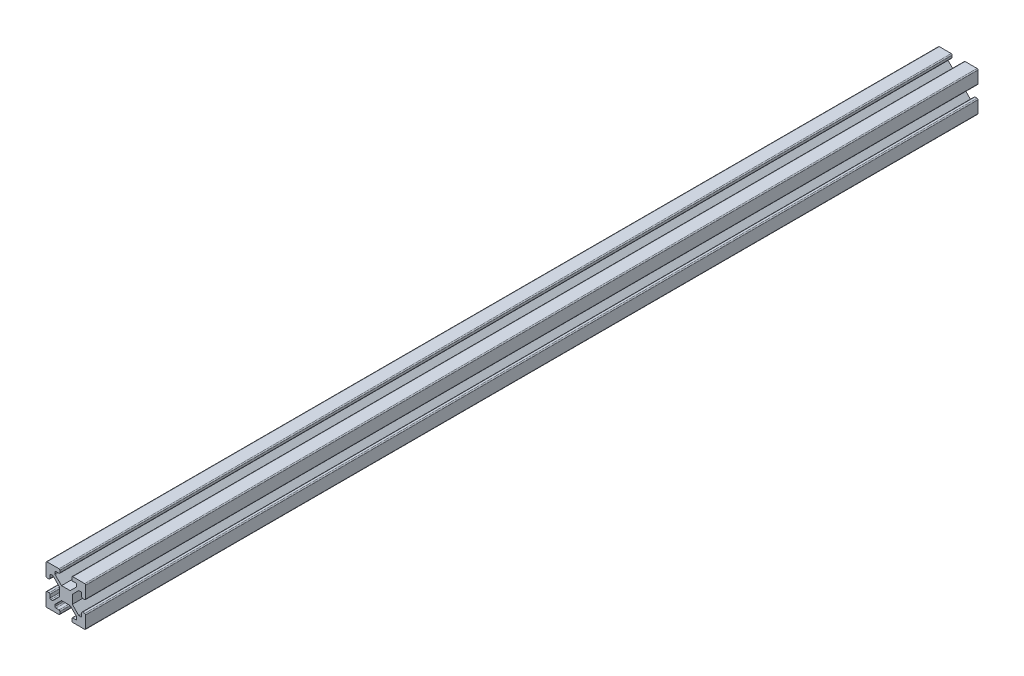
SolidWorks part; units mm, degrees
material "3.1645 (EN AW-2007)"
ref_plane "Front" through (0, 0, 0) normal (0, 0, 1) x (1, 0, 0)
ref_plane "Top" through (0, 0, 0) normal (0, 1, 0) x (1, 0, 0)
ref_plane "Right" through (0, 0, 0) normal (1, 0, 0) x (0, 0, -1)
sketch "草图1" plane through (0, 0, 0) normal (0, 0, 1) x (1, 0, 0)
  line L0 (6.5, 0) -> (0.5, 0)
  line L1 (20, -0.5) -> (20, -6.5)
  line L2 (19.5, -20) -> (13.5, -20)
  line L3 (20, -13.5) -> (20, -19.5)
  line L4 (13, -19.5) -> (13, -18.5)
  line L5 (13.5, -18) -> (15, -18)
  line L6 (15.5, -17.5) -> (15.5, -16.7791)
  line L7 (19.5, -7) -> (18.5, -7)
  line L8 (10, 0) -> (10, -26.2948) construction
  line L9 (18, -6.5) -> (18, -5)
  line L10 (17.5, -4.5) -> (16.7791, -4.5)
  line L11 (17.5, -15.5) -> (16.7791, -15.5)
  line L12 (18, -13.5) -> (18, -15)
  line L13 (19.5, -13) -> (18.5, -13)
  line L15 (0, -10) -> (20, -10) construction
  line L23 (4.5, -17.5) -> (4.5, -16.7791)
  line L24 (6.5, -18) -> (5, -18)
  line L25 (7, -19.5) -> (7, -18.5)
  line L27 (0.5, -20) -> (6.5, -20)
  line L29 (10, -20) -> (10, 6.2948) construction
  line L33 (0.5, -13) -> (1.5, -13)
  line L34 (2, -13.5) -> (2, -15)
  line L35 (2.5, -15.5) -> (3.2209, -15.5)
  line L36 (2.5, -4.5) -> (3.2209, -4.5)
  line L37 (2, -6.5) -> (2, -5)
  line L38 (0.5, -7) -> (1.5, -7)
  line L40 (7, -0.5) -> (7, -1.5)
  line L41 (6.5, -2) -> (5, -2)
  line L42 (4.5, -2.5) -> (4.5, -3.2209)
  line L43 (3.5745, -4.6464) -> (6.7416, -7.8136)
  line L44 (6.7416, -7.8136) -> (6.7416, -12.1864)
  line L45 (15.5, -2.5) -> (15.5, -3.2209)
  line L46 (13.5, -2) -> (15, -2)
  line L47 (13, -0.5) -> (13, -1.5)
  line L48 (19.5, 0) -> (13.5, 0)
  line L50 (10.3536, -10.3536) -> (20, -20) construction
  line L51 (4.6464, -3.5745) -> (7.8136, -6.7416)
  line L52 (7.8136, -6.7416) -> (12.1864, -6.7416)
  line L53 (0, -20) -> (9.6464, -10.3536) construction
  line L54 (15.3536, -3.5745) -> (12.1864, -6.7416)
  line L55 (13.2584, -7.8136) -> (13.2584, -12.1864)
  line L56 (16.4255, -4.6464) -> (13.2584, -7.8136)
  line L57 (10, 0) -> (10, -26.2948) construction
  line L58 (10, -20) -> (10, 6.2948) construction
  line L59 (16.4255, -15.3536) -> (13.2584, -12.1864)
  line L60 (15.3536, -16.4255) -> (12.3328, -13.4048)
  line L61 (8.0207, -13.2584) -> (11.9793, -13.2584)
  line L62 (4.6464, -16.4255) -> (7.6672, -13.4048)
  line L63 (3.5745, -15.3536) -> (6.7416, -12.1864)
  line L64 (0, -6.5) -> (0, -0.5)
  line L66 (0, -13.5) -> (0, -19.5)
  arc A0 (19.5, -7) -> (20, -6.5) centre (19.5, -6.5) ccw
  arc A1 (4.6464, -16.4255) -> (4.5, -16.7791) centre (5, -16.7791) ccw
  arc A2 (8.0207, -13.2584) -> (7.6672, -13.4048) centre (8.0207, -13.7584) ccw
  arc A3 (12.3328, -13.4048) -> (11.9793, -13.2584) centre (11.9793, -13.7584) ccw
  arc A4 (16.4255, -15.3536) -> (16.7791, -15.5) centre (16.7791, -15) ccw
  arc A5 (16.4255, -4.6464) -> (16.7791, -4.5) centre (16.7791, -5) cw
  arc A6 (15.3536, -16.4255) -> (15.5, -16.7791) centre (15, -16.7791) cw
  arc A7 (10.3536, -10.3536) -> (9.6464, -10.3536) centre (10, -10.7071) ccw construction
  arc A8 (15.3536, -3.5745) -> (15.5, -3.2209) centre (15, -3.2209) ccw
  arc A9 (3.5745, -15.3536) -> (3.2209, -15.5) centre (3.2209, -15) cw
  arc A10 (3.5745, -4.6464) -> (3.2209, -4.5) centre (3.2209, -5) ccw
  arc A11 (0.5, -7) -> (0, -6.5) centre (0.5, -6.5) cw
  arc A12 (2, -6.5) -> (1.5, -7) centre (1.5, -6.5) cw
  arc A13 (4.6464, -3.5745) -> (4.5, -3.2209) centre (5, -3.2209) cw
  arc A14 (2.5, -4.5) -> (2, -5) centre (2.5, -5) ccw
  arc A15 (2, -15) -> (2.5, -15.5) centre (2.5, -15) ccw
  arc A16 (1.5, -13) -> (2, -13.5) centre (1.5, -13.5) cw
  arc A17 (0.5, -13) -> (0, -13.5) centre (0.5, -13.5) ccw
  arc A18 (19.5, -13) -> (20, -13.5) centre (19.5, -13.5) cw
  arc A19 (13.5, 0) -> (13, -0.5) centre (13.5, -0.5) ccw
  arc A20 (13, -1.5) -> (13.5, -2) centre (13.5, -1.5) ccw
  arc A21 (15, -2) -> (15.5, -2.5) centre (15, -2.5) cw
  arc A22 (18, -13.5) -> (18.5, -13) centre (18.5, -13.5) cw
  arc A23 (4.5, -2.5) -> (5, -2) centre (5, -2.5) cw
  arc A24 (6.5, -2) -> (7, -1.5) centre (6.5, -1.5) ccw
  arc A25 (7, -0.5) -> (6.5, 0) centre (6.5, -0.5) ccw
  arc A26 (6.5, -18) -> (7, -18.5) centre (6.5, -18.5) cw
  arc A27 (4.5, -17.5) -> (5, -18) centre (5, -17.5) ccw
  arc A28 (17.5, -15.5) -> (18, -15) centre (17.5, -15) ccw
  arc A29 (15, -18) -> (15.5, -17.5) centre (15, -17.5) ccw
  arc A30 (13, -18.5) -> (13.5, -18) centre (13.5, -18.5) cw
  arc A31 (18, -5) -> (17.5, -4.5) centre (17.5, -5) ccw
  arc A32 (18.5, -7) -> (18, -6.5) centre (18.5, -6.5) cw
  arc A33 (19.5, 0) -> (20, -0.5) centre (19.5, -0.5) cw
  arc A34 (0.5, 0) -> (0, -0.5) centre (0.5, -0.5) ccw
  arc A35 (7, -19.5) -> (6.5, -20) centre (6.5, -19.5) cw
  arc A36 (13.5, -20) -> (13, -19.5) centre (13.5, -19.5) cw
  arc A37 (0.5, -20) -> (0, -19.5) centre (0.5, -19.5) cw
  arc A38 (20, -19.5) -> (19.5, -20) centre (19.5, -19.5) cw
  point P28 (4.5, -16.572)
  point P50 (10, -6.7416)
  point P56 (13.2584, -10)
  point P61 (6.7416, -10)
  point P62 (10, -13.2584)
  point P63 (7.8136, -13.2584)
  point P66 (12.1864, -13.2584)
  point P69 (16.572, -15.5)
  point P72 (16.572, -4.5)
  point P75 (15.5, -16.572)
  point P78 (10, -10)
  point P81 (15.5, -3.428)
  point P84 (3.428, -15.5)
  point P87 (3.428, -4.5)
  point P94 (4.5, -3.428)
  point P107 (13, 0)
  point P110 (13, -2)
  point P113 (15.5, -2)
  point P118 (4.5, -2)
  point P121 (7, -2)
  point P124 (7, 0)
  point P127 (7, -18)
  point P130 (4.5, -18)
  point P135 (15.5, -18)
  point P138 (13, -18)
  point P145 (20, 0)
  point P148 (0, 0)
  point P151 (7, -20)
  point P154 (13, -20)
extrude "凸台-拉伸1" add sketch "草图1" along normal blind 450
